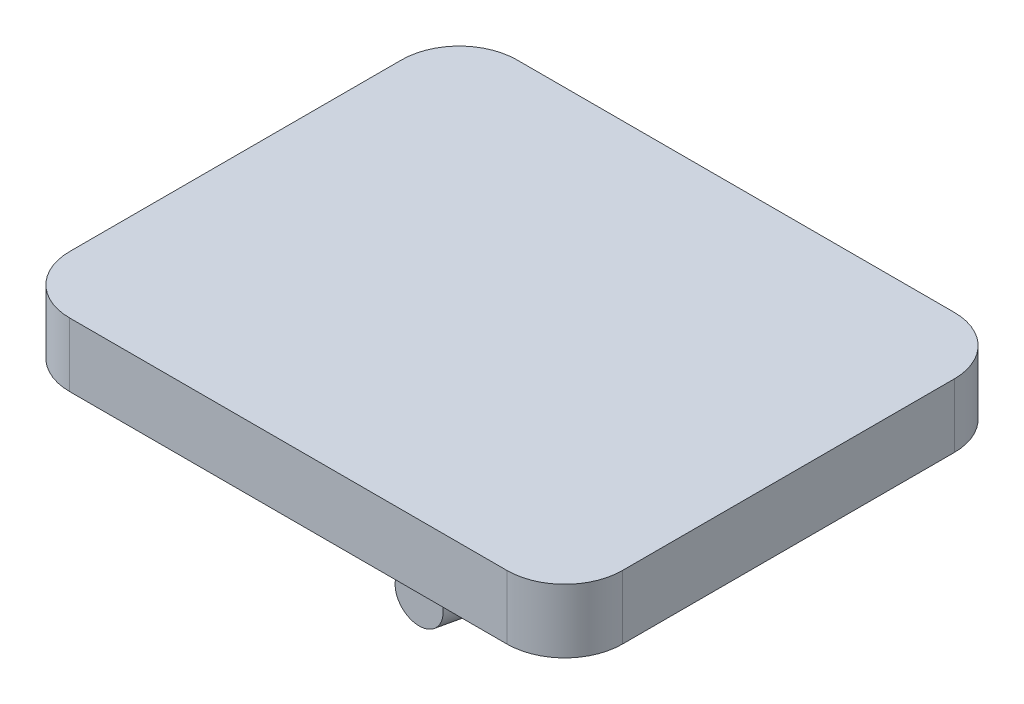
SolidWorks part; units mm, degrees
ref_plane "Front Plane" through (0, 0, 0) normal (0, 0, 1) x (1, 0, 0)
ref_plane "Top Plane" through (0, 0, 0) normal (0, 1, 0) x (1, 0, 0)
ref_plane "Right Plane" through (0, 0, 0) normal (1, 0, 0) x (0, 0, -1)
sketch "Sketch2" plane through (0, 0, 0) normal (0, 1, 0) x (1, 0, 0)
  line L0 (0, 116.4) -> (0, 0) construction
  line L1 (-143.85, -116.4) -> (143.85, -116.4)
  line L2 (-143.85, -116.4) -> (-143.85, 116.4)
  line L3 (-143.85, 116.4) -> (143.85, 116.4)
  line L4 (143.85, -116.4) -> (143.85, 116.4)
  line L5 (0, 0) -> (143.85, 0) construction
  arc A0 (-143.85, 86.4) -> (-113.85, 116.4) centre (-113.85, 86.4) cw
  arc A1 (143.85, 86.4) -> (113.85, 116.4) centre (113.85, 86.4) ccw
  arc A2 (143.85, -86.4) -> (113.85, -116.4) centre (113.85, -86.4) cw
  arc A3 (-143.85, -86.4) -> (-113.85, -116.4) centre (-113.85, -86.4) ccw
  dimension "D3" = 30
  dimension "D1" = 232.8
  dimension "D2" = 287.7
extrude "Boss-Extrude1" add sketch "Sketch2" along normal blind 33.2 contours L2 A3 L1 A2 L4 A1 L3 A0
ref_plane "Plane1" through (39.95, 0, 0) normal (1, 0, 0) x (0, 0, -1)
sketch "Sketch3" plane through (39.95, 0, 0) normal (1, 0, 0) x (0, 0, -1)
  line L0 (85.6, 0) -> (85.6, -30.3) construction
  line L1 (-86.4, 0) -> (86.4, 0) construction
  line L2 (-86.4, 33.2) -> (86.4, 33.2) construction
  line L3 (116.4, 33.2) -> (116.4, 0) construction
  line L4 (85.6, -30.3) -> (-88.3, -30.3)
  line L5 (85.6, -30.3) -> (85.6, -5.3)
  line L6 (85.6, -5.3) -> (-88.3, -5.3)
  line L7 (-88.3, -30.3) -> (-88.3, -5.3)
  line L8 (-88.3, -17.8) -> (-1.35, -5.3)
  dimension "D1" = 63.5
  dimension "D2" = 25
  dimension "D3" = 30.8
  dimension "D4" = 173.9
revolve "Revolve2" add sketch "Sketch3" angle 360 about L4
sketch "Sketch4" plane through (39.95, 0, 0) normal (1, 0, 0) x (0, 0, -1)
  line L1 (0, 0) -> (83.5117, 0)
  line L2 (0, 0) -> (0, -9.1346)
  line L3 (0, -9.1346) -> (83.5117, -9.1346)
  line L4 (83.5117, 0) -> (83.5117, -9.1346)
extrude "Boss-Extrude2" add sketch "Sketch4" along normal blind 5 and the other way blind 5
sketch "Sketch5" plane through (0, 0, 0) normal (0, -1, 0) x (1, 0, 0)
  line L0 (-113.85, -116.4) -> (113.85, -116.4) construction
  line L1 (-143.85, 86.4) -> (-143.85, -86.4) construction
  circle A0 centre (-108.35, -70) radius 32
  dimension "D1" = 64
  dimension "D2" = 46.4
  dimension "D3" = 35.5
extrude "Boss-Extrude3" add sketch "Sketch5" along normal blind 5
sketch "Sketch6" plane through (0, 0, 0) normal (0, -1, 0) x (1, 0, 0)
  line L1 (113.85, 86.4) -> (-113.85, 86.4) construction
  line L2 (113.85, 86.4) -> (113.85, -86.4) construction
  line L3 (113.85, -86.4) -> (-113.85, -86.4) construction
  line L4 (-113.85, 86.4) -> (-113.85, -86.4) construction
  line L5 (113.85, 86.4) -> (-113.85, -86.4) construction
  line L6 (113.85, -86.4) -> (-113.85, 86.4) construction
  circle A0 centre (113.85, -86.4) radius 2.5
  circle A1 centre (0, -86.4) radius 2.5
  circle A2 centre (113.85, 86.4) radius 2.5
  circle A3 centre (0, 86.4) radius 2.5
  circle A4 centre (-113.85, 86.4) radius 2.5
  arc A5 (113.85, -116.4) -> (143.85, -86.4) centre (113.85, -86.4) ccw construction
  point P0 (0, 0)
  dimension "D1" = 5
extrude "Cut-Extrude1" cut sketch "Sketch6" against normal blind 5
sketch "Sketch7" plane through (0, 0, 0) normal (0, -1, 0) x (1, 0, 0)
  line L0 (0, 86.4) -> (-113.85, 86.4) construction
  line L1 (0, 79.9) -> (-113.85, 79.9)
  line L2 (0, 92.9) -> (-113.85, 92.9)
  line L3 (6.5, 86.4) -> (-120.35, 86.4) construction
  arc A0 (0, 79.9) -> (0, 92.9) centre (0, 86.4) ccw
  arc A1 (-113.85, 92.9) -> (-113.85, 79.9) centre (-113.85, 86.4) ccw
  circle A2 centre (0, 86.4) radius 2.75
  circle A3 centre (-113.85, 86.4) radius 2.75
  point P4 (-56.925, 86.4)
  dimension "D1" = 6.5
  dimension "D2" = 5.5
  dimension "D3" = 126.85
extrude "Boss-Extrude4" [suppressed] add sketch "Sketch7" along normal blind 4.8
sketch "Sketch8" [suppressed] plane through (0, -4.8, 0) normal (0, -1, 0) x (1, 0, 0)
  line L0 (-56.925, 79.9) -> (-56.925, 92.9) construction
  line L1 (-113.85, 79.9) -> (0, 79.9) construction
  line L2 (0, 92.9) -> (-113.85, 92.9) construction
  line L3 (-56.925, 92.9) -> (-56.925, 86.4) construction
  line L4 (-56.925, 86.4) -> (6.5, 86.4) construction
  arc A0 (0, 79.9) -> (0, 92.9) centre (0, 86.4) ccw construction
  circle A1 centre (-56.925, 86.4) radius 3.45
  circle A2 centre (-42.85, 86.4) radius 2.75
  circle A3 centre (-28.85, 86.4) radius 3.45
  circle A4 centre (-10, 83.65) radius 2.35
  circle A6 centre (-71, 86.4) radius 2.75
  circle A7 centre (-85, 86.4) radius 3.45
  circle A8 centre (-103.85, 83.65) radius 2.35
  point P18 (0, 86.4)
  dimension "D1" = 6.9
  dimension "D2" = 5.5
  dimension "D3" = 4.7
  dimension "D4" = 10
  dimension "D5" = 28.85
  dimension "D6" = 42.85
  dimension "D7" = 56.925
  dimension "D8" = 2.75
extrude "Cut-Extrude2" [suppressed] cut sketch "Sketch8" against normal blind 4.8
